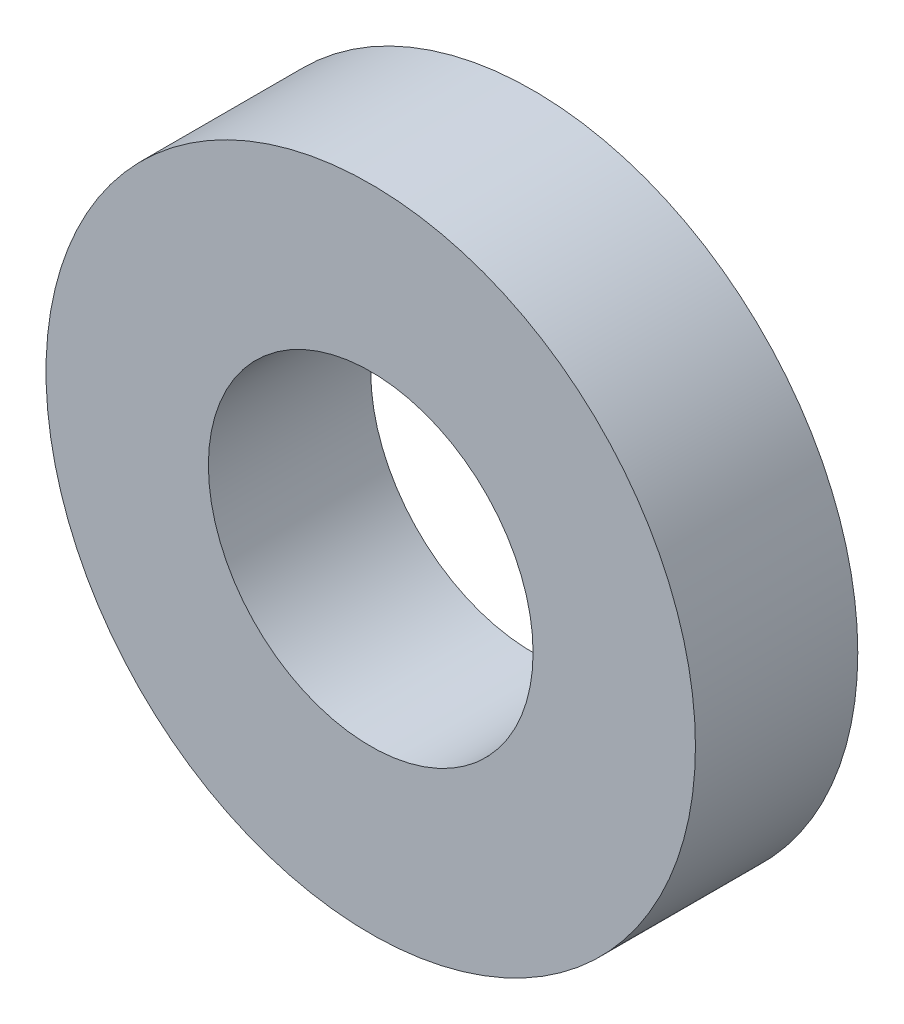
SolidWorks part; units mm, degrees
material "硅橡胶"
ref_plane "前视基准面" through (0, 0, 0) normal (0, 0, 1) x (1, 0, 0)
ref_plane "上视基准面" through (0, 0, 0) normal (0, 1, 0) x (1, 0, 0)
ref_plane "右视基准面" through (0, 0, 0) normal (1, 0, 0) x (0, 0, -1)
sketch "草图1" plane through (0, 0, 0) normal (0, 0, 1) x (1, 0, 0)
  circle A0 centre (0, 0) radius 4
  circle A1 centre (0, 0) radius 8
extrude "凸台-拉伸1" add sketch "草图1" along normal blind 4
